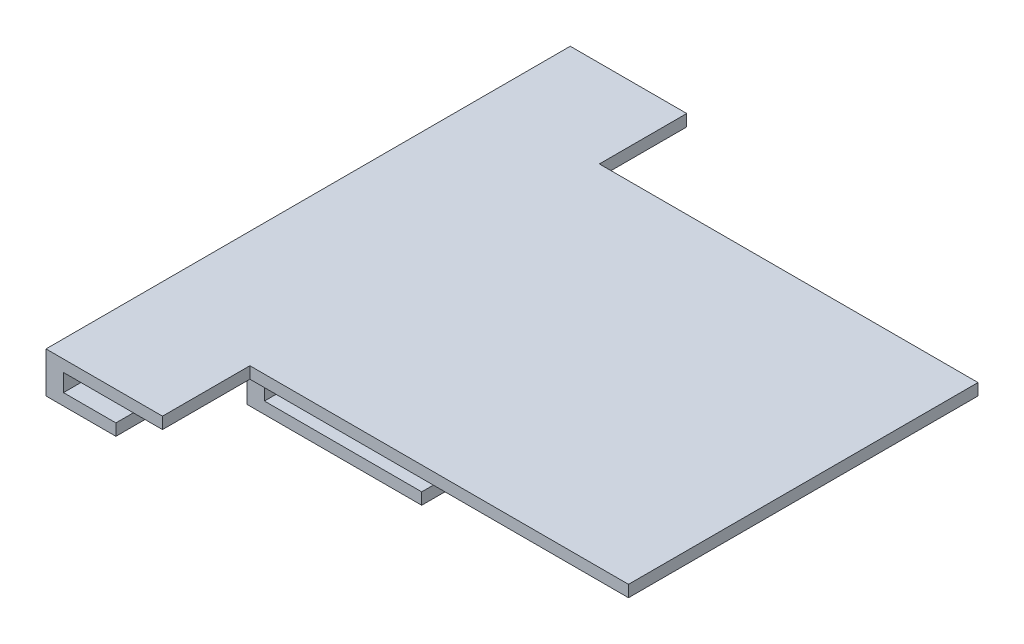
SolidWorks part; units mm, degrees
ref_plane "Front" through (0, 0, 0) normal (0, 0, 1) x (1, 0, 0)
ref_plane "Top" through (0, 0, 0) normal (0, 1, 0) x (1, 0, 0)
ref_plane "Right" through (0, 0, 0) normal (1, 0, 0) x (0, 0, -1)
sketch "Sketch1" plane through (0, 0, 0) normal (0, 1, 0) x (1, 0, 0)
  line L0 (-44.1556, 0) -> (63.2566, 0) construction
  line L2 (-22.5, 30) -> (42.5, 30)
  line L3 (-42.5, 30) -> (-42.5, -30)
  line L4 (-22.5, -30) -> (42.5, -30)
  line L5 (42.5, 30) -> (42.5, -30)
  line L6 (-42.5, 30) -> (42.5, -30) construction
  line L7 (-42.5, -30) -> (42.5, 30) construction
  line L9 (-42.5, 30) -> (-42.5, 45)
  line L10 (-42.5, 45) -> (-22.5, 45)
  line L11 (-22.5, 30) -> (-22.5, 45)
  line L13 (-42.5, -30) -> (-42.5, -45)
  line L14 (-42.5, -45) -> (-22.5, -45)
  line L15 (-22.5, -30) -> (-22.5, -45)
  point P3 (0, 0)
  dimension "D1" = 60
  dimension "D2" = 85
  dimension "D3" = 15
  dimension "D4" = 15
  dimension "D5" = 20
  dimension "D6" = 20
extrude "Boss-Extrude1" add sketch "Sketch1" along normal blind 2
sketch "Sketch2" plane through (0, 0, 0) normal (0, -1, 0) x (1, 0, 0)
  line L0 (-42.5, 0) -> (42.5, 0) construction
  line L1 (-42.5, -45) -> (-42.5, 45) construction
  line L2 (42.5, 30) -> (42.5, -30) construction
  line L3 (-22.5, 30) -> (-22.5, -30) construction
  line L4 (-42.5, -45) -> (-39.5, -45)
  line L5 (-24, 29) -> (-21, 29)
  line L6 (-24, 29) -> (-24, -29)
  line L7 (-24, -29) -> (-21, -29)
  line L8 (-21, 29) -> (-21, -29)
  line L9 (-24, 29) -> (-21, -29) construction
  line L10 (-24, -29) -> (-21, 29) construction
  line L11 (-42.5, 45) -> (-39.5, 45)
  line L12 (-42.5, 45) -> (-42.5, 29.5)
  line L13 (-42.5, 29.5) -> (-40.5243, 29.5)
  line L14 (-39.5, 45) -> (-39.5, 32.5)
  line L15 (-40.5243, 29.5) -> (-30.5, 29.5)
  line L16 (-39.5, -45) -> (-39.5, -32.5)
  line L17 (-39.5, 32.5) -> (-30.5, 32.5)
  line L18 (-30.5, 29.5) -> (-30.5, 32.5)
  line L19 (-30.5, -29.5) -> (-30.5, -32.5)
  line L20 (-39.5, -32.5) -> (-30.5, -32.5)
  line L21 (-40.5243, -29.5) -> (-30.5, -29.5)
  line L22 (-42.5, -29.5) -> (-40.5243, -29.5)
  line L23 (-42.5, -45) -> (-42.5, -29.5)
  point P10 (-22.5, 0)
  dimension "D1" = 58
  dimension "D2" = 3
  dimension "D3" = 12
  dimension "D4" = 3
  dimension "D5" = 3
  dimension "D6" = 65
extrude "Boss-Extrude2" add sketch "Sketch2" along normal blind 3
sketch "Sketch3" plane through (0, -3, 0) normal (0, -1, 0) x (1, 0, 0)
  line L1 (-42.5, 45) -> (-30.5, 45)
  line L2 (-42.5, 45) -> (-42.5, 29.5)
  line L3 (-42.5, 29.5) -> (-30.5, 29.5)
  line L4 (-30.5, 45) -> (-30.5, 29.5)
  line L5 (-30.5, -29.5) -> (-42.5, -29.5)
  line L6 (-30.5, -29.5) -> (-30.5, -45)
  line L7 (-30.5, -45) -> (-42.5, -45)
  line L8 (-42.5, -29.5) -> (-42.5, -45)
  line L9 (-24, 29) -> (6, 29)
  line L10 (-24, 29) -> (-24, -29)
  line L11 (-24, -29) -> (6, -29)
  line L12 (6, 29) -> (6, -29)
  dimension "D1" = 30
extrude "Boss-Extrude3" add sketch "Sketch3" along normal blind 2
